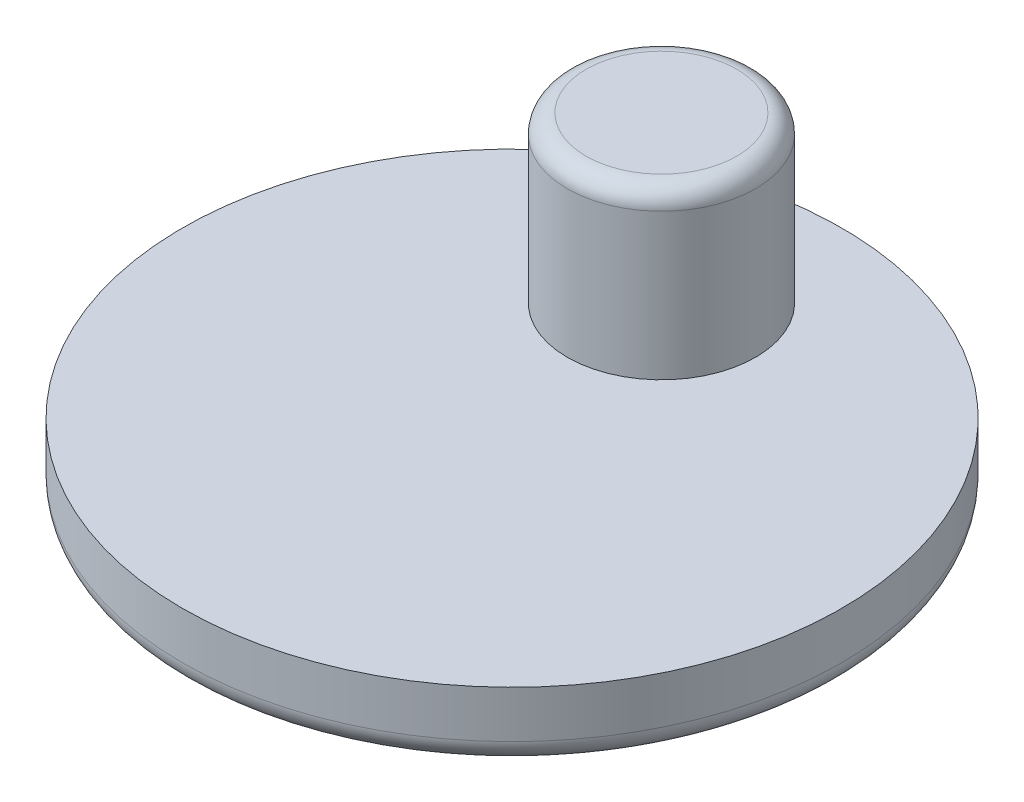
SolidWorks part; units mm, degrees
ref_plane "Front Plane" through (0, 0, 0) normal (0, 0, 1) x (1, 0, 0)
ref_plane "Top Plane" through (0, 0, 0) normal (0, 1, 0) x (1, 0, 0)
ref_plane "Right Plane" through (0, 0, 0) normal (1, 0, 0) x (0, 0, -1)
sketch "Sketch1" plane through (0, 0, 0) normal (0, 1, 0) x (1, 0, 0)
  line L0 (0, 7) -> (6.51, 7) construction
  circle A0 centre (0, 0) radius 7
  dimension "D1" = 14
extrude "Boss-Extrude1" add sketch "Sketch1" along normal blind 1.5
sketch "Sketch2" plane through (-0.5192, 1.5, -6.2069) normal (0, 1, 0) x (1, 0, 0)
  circle A0 centre (-0.0136, -2.5015) radius 2
  circle A1 centre (-0.0136, -2.5015) radius 2 construction
  dimension "D1" = 4
  dimension "D2" = 0
extrude "Boss-Extrude2" add sketch "Sketch2" along normal blind 3.5
fillet "Fillet1" radius 0.4 1 edges at (-0.5327, 5, -1.7054)
fillet "Fillet2" radius 0.5 1 edges at (0, 0, 7)
